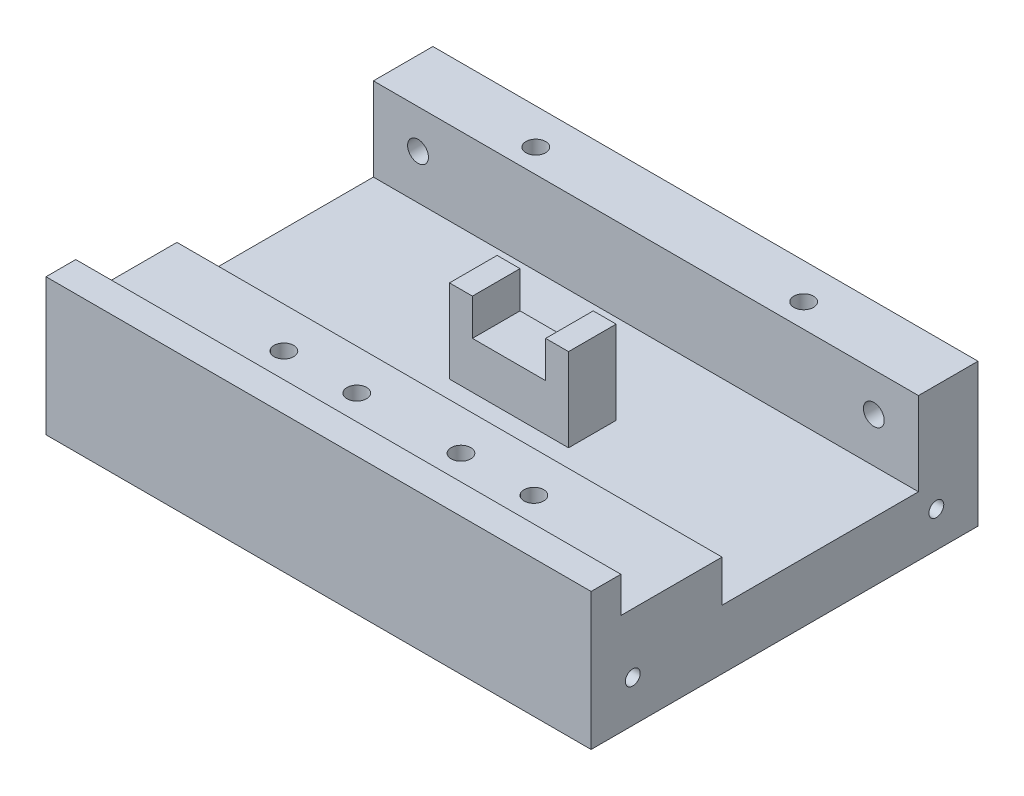
SolidWorks part; units mm, degrees
ref_plane "Front Plane" through (0, 0, 0) normal (0, 0, 1) x (1, 0, 0)
ref_plane "Top Plane" through (0, 0, 0) normal (0, 1, 0) x (1, 0, 0)
ref_plane "Right Plane" through (0, 0, 0) normal (1, 0, 0) x (0, 0, -1)
sketch "Sketch1" plane through (0, 0, 0) normal (0, 0, 1) x (1, 0, 0)
  line L1 (-38.29, 27.56) -> (38.29, 27.56) construction
  line L2 (-38.29, 27.56) -> (-38.29, -27.56) construction
  line L3 (-38.29, -27.56) -> (38.29, -27.56) construction
  line L4 (38.29, 27.56) -> (38.29, -27.56) construction
  line L5 (-38.29, 27.56) -> (38.29, -27.56) construction
  line L6 (-38.29, -27.56) -> (38.29, 27.56) construction
  line L7 (-45.79, 35.06) -> (45.79, 35.06)
  line L8 (-45.79, 35.06) -> (-45.79, -35.06)
  line L9 (-45.79, -35.06) -> (45.79, -35.06)
  line L10 (45.79, 35.06) -> (45.79, -35.06)
  circle A0 centre (-16.8254, 27.05) radius 1.75
  circle A1 centre (33.464, 27.56) radius 1.75
  circle A2 centre (38.29, -27.56) radius 1.75
  circle A3 centre (-38.29, -27.56) radius 1.75
  point P0 (0, 0)
  point P6 (33.464, 27.56)
  point P7 (-16.8254, 27.05)
  dimension "D6" = 3.5
  dimension "D1" = 76.58
  dimension "D2" = 55.12
  dimension "D3" = 4.826
  dimension "D4" = 50.292
  dimension "D5" = 54.61
  dimension "D7" = 7.5
  dimension "D8" = 7.5
  dimension "D9" = 7.5
  dimension "D10" = 7.5
extrude "Boss-Extrude1" add sketch "Sketch1" along normal blind 10
sketch "Sketch2" plane through (0, -35.06, 0) normal (0, -1, 0) x (1, 0, 0)
  line L1 (-45.79, 0) -> (45.79, 0)
  line L2 (-45.79, 0) -> (-45.79, 65)
  line L3 (-45.79, 65) -> (45.79, 65)
  line L4 (45.79, 0) -> (45.79, 65)
  dimension "D1" = 65
extrude "Boss-Extrude2" add sketch "Sketch2" along normal blind 10
sketch "Sketch3" plane through (0, -35.06, 0) normal (0, 1, 0) x (1, 0, 0)
  line L1 (-10, -25) -> (10, -25)
  line L2 (-10, -25) -> (-10, -33)
  line L3 (-10, -33) -> (10, -33)
  line L4 (10, -25) -> (10, -33)
  line L6 (0, 0) -> (0, -33) construction
  line L7 (-45.79, -10) -> (45.79, -10) construction
  dimension "D1" = 20
  dimension "D2" = 15
  dimension "D3" = 8
extrude "Boss-Extrude3" add sketch "Sketch3" along normal blind 14
sketch "Sketch4" plane through (0, 0, 25) normal (0, 0, -1) x (-1, 0, 0)
  line L0 (-45.79, -35.06) -> (45.79, -35.06) construction
  line L1 (6.15, -21.06) -> (6.15, -14.91)
  line L2 (6.15, -14.91) -> (-6.15, -14.91)
  line L3 (-6.15, -14.91) -> (-6.15, -21.06)
  line L4 (6.15, -21.06) -> (6.15, -27.21)
  line L5 (6.15, -27.21) -> (-6.15, -27.21)
  line L6 (-6.15, -27.21) -> (-6.15, -21.06)
  arc A0 (-6.15, -21.06) -> (6.15, -21.06) centre (0, -21.06) ccw construction
  dimension "D1" = 12.3
  dimension "D2" = 14
extrude "Cut-Extrude1" cut sketch "Sketch4" against normal blind 75
sketch "Sketch6" plane through (0, -21.06, 0) normal (0, 1, 0) x (1, 0, 0)
  line L1 (-45.79, 0) -> (45.79, 0)
  line L2 (-45.79, 0) -> (-45.79, -65)
  line L3 (-45.79, -65) -> (45.79, -65)
  line L4 (45.79, 0) -> (45.79, -65)
extrude "Cut-Extrude3" cut sketch "Sketch6" along normal through all
sketch "Sketch11" plane through (0, -35.06, 0) normal (0, 1, 0) x (1, 0, 0)
  line L0 (45.79, -65) -> (-45.79, -65) construction
  line L1 (45.79, -65) -> (-45.79, -65)
  line L2 (45.79, -65) -> (45.79, -43)
  line L3 (45.79, -43) -> (-45.79, -43)
  line L4 (-45.79, -65) -> (-45.79, -43)
  line L5 (0, 0) -> (0, -43) construction
  line L6 (45.79, 0) -> (-45.79, 0) construction
  line L7 (-45.79, -65) -> (-45.79, -10) construction
  dimension "D1" = 22
extrude "Boss-Extrude4" add sketch "Sketch11" along normal blind 7
sketch "Sketch12" plane through (0, -28.06, 0) normal (0, 1, 0) x (1, 0, 0)
  line L0 (-45.79, -43) -> (-45.79, -65) construction
  line L1 (45.79, -65) -> (-45.79, -65)
  line L2 (45.79, -65) -> (45.79, -60)
  line L3 (45.79, -60) -> (-45.79, -60)
  line L4 (-45.79, -65) -> (-45.79, -60)
  dimension "D1" = 5
extrude "Boss-Extrude5" add sketch "Sketch12" along normal blind 6
sketch "Sketch15" plane through (0, -28.06, 0) normal (0, 1, 0) x (1, 0, 0)
  line L0 (-21, -49.825) -> (21, -49.825) construction
  line L2 (0, -49.825) -> (0, 0) construction
  line L4 (-45.79, -65) -> (45.79, -65) construction
  point P0 (21, -49.825)
  point P2 (-21, -49.825)
  dimension "D1" = 15.175
  dimension "D2" = 42
hole_wizard "M4 Tapped Hole2" positions "Sketch15" profile "Sketch14" tap size "M4" standard "ISO"
cosmetic thread "Hole Thread2" parameters "D1"=18, "D2"=4
cosmetic thread "Hole Thread3" parameters "D1"=18, "D2"=4
sketch "Sketch14" plane through (21, -28.06, 49.825) normal (1, 0, 0) x (0, 0, 1)
  line L0 (0, 0) -> (0, 10.9914)
  line L1 (0, 10.9914) -> (1.65, 10)
  line L2 (1.65, 10) -> (1.65, 0)
  line L5 (1.65, 0) -> (0, 0)
  line L10 (0, 10.9914) -> (-1.65, 10) construction
  line L11 (0, -6.35) -> (0, 107.95) construction
  dimension "Tap Drill Dia." = 3.3
  dimension "Tap Drill Depth" = 10
  dimension "Drill Angle" = 118
sketch "Sketch16" plane through (0, -45.06, 0) normal (0, -1, 0) x (1, 0, 0)
  line L0 (8.75, 49.825) -> (-8.75, 49.825) construction
  line L1 (-21, 49.825) -> (21, 49.825) construction
  circle A0 centre (-8.75, 49.825) radius 4.25
  circle A1 centre (8.75, 49.825) radius 4.25
  circle A2 centre (-21, 49.825) radius 1.65 construction
  circle A3 centre (21, 49.825) radius 1.65 construction
  circle A4 centre (-21, 49.825) radius 1.65 construction
  circle A5 centre (21, 49.825) radius 1.65 construction
  point P10 (0, 49.825)
  point P11 (0, 49.825)
  dimension "D1" = 17.5
  dimension "D2" = 8.5
extrude "Cut-Extrude4" cut sketch "Sketch16" against normal blind 12
sketch "Sketch19" plane through (0, -33.06, 0) normal (0, -1, 0) x (-1, 0, 0)
  point P0 (8.75, -49.825)
  point P3 (-8.75, -49.825)
hole_wizard "M4 Tapped Hole3" positions "Sketch19" profile "Sketch20" tap size "M4" standard "ISO" end condition through all
sketch "Sketch20" plane through (-8.75, -33.06, 49.825) normal (1, 0, 0) x (0, 0, -1)
  line L0 (0, 0) -> (0, 12)
  line L1 (0, 12) -> (1.65, 12)
  line L2 (1.65, 12) -> (1.65, 0)
  line L5 (1.65, 0) -> (0, 0)
  line L11 (0, -6.35) -> (0, 107.95) construction
  dimension "Thru Tap Drill Dia." = 3.3
  dimension "Thru Tap Drill Depth" = 12
cosmetic thread "Hole Thread4" parameters "D2"=4
cosmetic thread "Hole Thread5" parameters "D2"=4
sketch "Sketch21" plane through (0, 0, 0) normal (0, 0, -1) x (-1, 0, 0)
  circle A0 centre (-38.29, -27.56) radius 3.5
  circle A1 centre (38.29, -27.56) radius 3.5
  dimension "D1" = 7
extrude "Cut-Extrude5" cut sketch "Sketch21" against normal blind 4
sketch "Sketch24" plane through (0, -21.06, 0) normal (0, 1, 0) x (1, 0, 0)
  line L0 (-45.79, -6) -> (45.79, -6) construction
  line L4 (0, 0) -> (0, -6) construction
  line L5 (45.79, 0) -> (-45.79, 0) construction
  line L7 (-22.5, -6) -> (22.5, -6) construction
  line L9 (45.79, -10) -> (45.79, 0) construction
  point P0 (-22.5, -6)
  point P2 (22.5, -6)
  dimension "D1" = 45
  dimension "D2" = 6
hole_wizard "M4 Tapped Hole4" positions "Sketch24" profile "Sketch25" tap size "M4" standard "ISO"
sketch "Sketch25" plane through (-22.5, -21.06, 6) normal (1, 0, 0) x (0, 0, 1)
  line L0 (0, 0) -> (0, 15.9914)
  line L1 (0, 15.9914) -> (1.65, 15)
  line L2 (1.65, 15) -> (1.65, 0)
  line L5 (1.65, 0) -> (0, 0)
  line L10 (0, 15.9914) -> (-1.65, 15) construction
  line L11 (0, -6.35) -> (0, 107.95) construction
  dimension "Tap Drill Dia." = 3.3
  dimension "Tap Drill Depth" = 15
  dimension "Drill Angle" = 118
cosmetic thread "Hole Thread6" parameters "D1"=8, "D2"=4
cosmetic thread "Hole Thread7" parameters "D1"=8, "D2"=4
sketch "Sketch28" plane through (-45.79, 0, 0) normal (-1, 0, 0) x (0, 0, 1)
  line L0 (65, -45.06) -> (65, -22.06) construction
  line L1 (65, -45.06) -> (0, -45.06) construction
  line L2 (0, -21.06) -> (0, -45.06) construction
  point P0 (58, -38.06)
  point P2 (7, -39.06)
  dimension "D1" = 7
  dimension "D2" = 7
  dimension "D3" = 6
  dimension "D4" = 7
hole_wizard "M3 Tapped Hole1" positions "Sketch28" profile "Sketch27" tap size "M3" standard "ISO"
sketch "Sketch27" plane through (-45.79, -38.06, 58) normal (0, 1, 0) x (0, 0, 1)
  line L0 (0, 0) -> (0, 8.2511)
  line L1 (0, 8.2511) -> (1.25, 7.5)
  line L2 (1.25, 7.5) -> (1.25, 0)
  line L5 (1.25, 0) -> (0, 0)
  line L10 (0, 8.2511) -> (-1.25, 7.5) construction
  line L11 (0, -6.35) -> (0, 107.95) construction
  dimension "Tap Drill Dia." = 2.5
  dimension "Tap Drill Depth" = 7.5
  dimension "Drill Angle" = 118
cosmetic thread "Hole Thread8" parameters "D1"=6, "D2"=3
cosmetic thread "Hole Thread9" parameters "D1"=6, "D2"=3
mirror "Mirror1" about plane through (0, 0, 0) normal (1, 0, 0) of "M3 Tapped Hole1"
cosmetic thread "Hole Thread10" parameters "D1"=6, "D2"=3
cosmetic thread "Hole Thread11" parameters "D1"=6, "D2"=3
